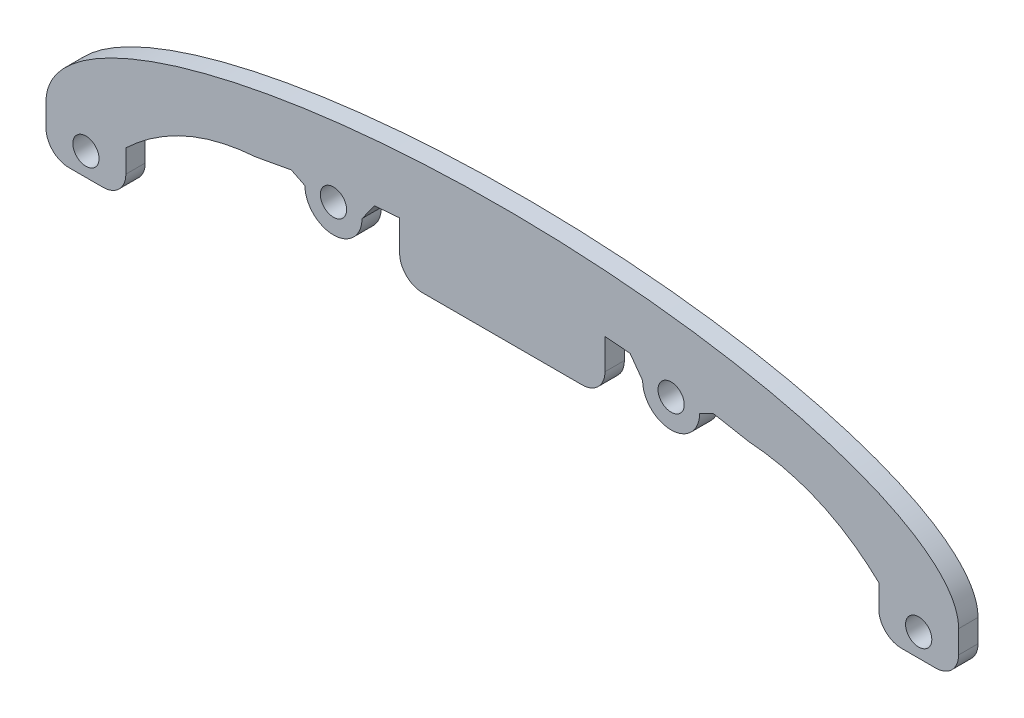
SolidWorks part; units mm, degrees
ref_plane "Płaszczyzna przednia" through (0, 0, 0) normal (0, 0, 1) x (1, 0, 0)
ref_plane "Płaszczyzna górna" through (0, 0, 0) normal (0, 1, 0) x (1, 0, 0)
ref_plane "Płaszczyzna prawa" through (0, 0, 0) normal (1, 0, 0) x (0, 0, -1)
sketch "Szkic1" plane through (0, 0, 0) normal (0, 0, 1) x (1, 0, 0)
  line L6 (-21.6102, 5) -> (21.6102, 5) construction
  line L7 (-40, 0) -> (40, 0) construction
  line L8 (0, 26.284) -> (0, -11.2038) construction
  line L9 (-12.3, 4.9798) -> (-11.2, 6.5001)
  line L11 (-9, 6.6798) -> (-9, 2)
  line L12 (-9, 2) -> (9, 2)
  line L13 (9, 6.6798) -> (9, 2)
  line L14 (-17.3, 4.9798) -> (-18.5, 5.5751)
  line L15 (12.3, 4.9798) -> (11.2, 6.5001)
  line L16 (17.3, 4.9798) -> (18.5, 5.5751)
  line L17 (-40, 0) -> (-40, -4)
  line L18 (-40, -4) -> (-33, -4)
  line L19 (-33, -4) -> (-33, 0)
  line L20 (33, 0) -> (33, -4)
  line L21 (33, -4) -> (40, -4)
  line L22 (40, -4) -> (40, 0)
  arc A2 (-17.3, 4.9798) -> (-12.3, 4.9798) centre (-14.8, 4.9798) ccw
  arc A3 (12.3, 4.9798) -> (17.3, 4.9798) centre (14.8, 4.9798) ccw
  ellipse E0 centre (0, 0) end of major axis (-40, 0) minor radius 12 (40, 0) -> (-40, 0) ccw
  spline S0 degree 1 poles (21.6102, 5) (-21.6102, 5) knots 0 0 1 1 construction
  spline S1 degree 3 poles (21.6102, 5) (21.218, 5.0807) (20.4395, 5.2344) (19.4951, 5.406) (18.742, 5.5353) (17.912, 5.6726) (15.627, 6.023) (13.0948, 6.3274) (10.8372, 6.5336) (10.1054, 6.5952) (9.3703, 6.6535) (7.9311, 6.7574) (4.7685, 6.9358) (0, 7.0436) (-4.7685, 6.9358) (-7.9311, 6.7574) (-9.3703, 6.6535) (-10.1054, 6.5952) (-10.8372, 6.5336) (-13.0948, 6.3274) (-15.627, 6.023) (-17.912, 5.6726) (-18.742, 5.5353) (-19.4951, 5.406) (-20.4395, 5.2344) (-21.218, 5.0807) (-21.6102, 5) knots -2.17176 -2.17176 -2.17176 -2.17176 -2.1342 -2.096639 -2.084153 -2.065373 -2.021519 -1.881328 -1.851592 -1.836724 -1.821856 -1.792121 -1.721037 -1.570796 -1.420555 -1.349472 -1.319736 -1.304868 -1.290001 -1.260265 -1.120074 -1.07622 -1.05744 -1.044953 -1.007393 -0.969833 -0.969833 -0.969833 -0.969833
  spline S2 degree 2 poles (-21.6102, 5) (-28.2034, 4.5386) (-33, 0) knots 0 0 0 1 1 1
  spline S3 degree 2 poles (21.6102, 5) (28.2034, 4.5386) (33, 0) knots 0 0 0 1 1 1
  point P34 (0, 0)
  point P36 (0, 0)
  point P37 (0, 0)
  dimension "D8" = 12.7
  dimension "D9" = 12.7
  dimension "D14" = 5
  dimension "D15" = 5
  dimension "D2" = 80
  dimension "D3" = 7
  dimension "D4" = 4
  dimension "D5" = 12
  dimension "D6" = 3.5
  dimension "D7" = 1.5
  dimension "D10" = 3.5
  dimension "D11" = 10
  dimension "D12" = 9
  dimension "D13" = 9
  dimension "D16" = 3.7
  dimension "D17" = 2.2
  dimension "D18" = 3.3
  dimension "D19" = 2.2
  dimension "D20" = 8.3
  dimension "D21" = 1.7
  dimension "D22" = 3.3
  dimension "D23" = 3.7
  dimension "D1" = 5
extrude "Dodanie-wyciągnięcie1" add sketch "Szkic1" along normal blind 1.7
sketch "Szkic2" plane through (0, 0, 1.7) normal (0, 0, 1) x (1, 0, 0)
  line L0 (-33, -4) -> (-33, 0) construction
  line L1 (33, 0) -> (33, -4) construction
  line L2 (33, -4) -> (40, -4) construction
  line L3 (-40, -4) -> (-33, -4) construction
  circle A0 centre (-14.8, 4.9798) radius 1.15
  circle A1 centre (14.8, 4.9798) radius 1.15
  circle A2 centre (-36.5, -2) radius 1.15
  circle A3 centre (36.5, -2) radius 1.15
  dimension "D1" = 2.3
  dimension "D2" = 2.3
  dimension "D3" = 2.3
  dimension "D4" = 2.3
  dimension "D5" = 3.5
  dimension "D6" = 3.5
  dimension "D7" = 2
  dimension "D8" = 2
extrude "Wytnij-wyciągnięcie1" cut sketch "Szkic2" against normal through all
fillet "Zaokrąglenie1" radius 2 6 edges at (-40, -4, 0.85) (-33, -4, 0.85) (9, 2, 0.85) (-9, 2, 0.85) (40, -4, 0.85) (33, -4, 0.85)
